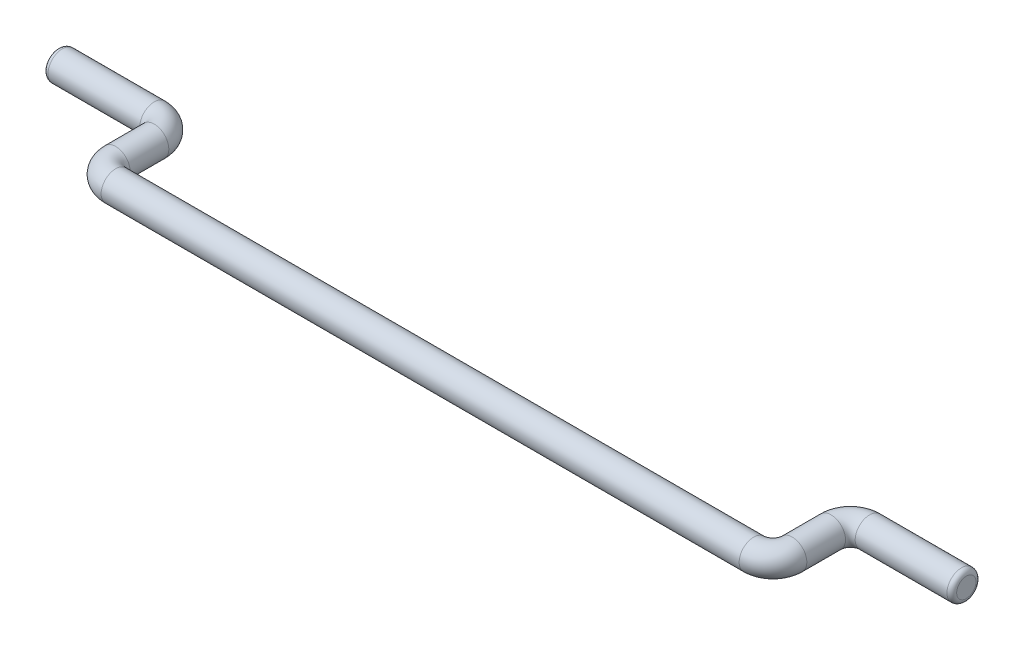
SolidWorks part; units mm, degrees
ref_plane "Front Plane" through (0, 0, 0) normal (0, 0, 1) x (1, 0, 0)
ref_plane "Top Plane" through (0, 0, 0) normal (0, 1, 0) x (1, 0, 0)
ref_plane "Right Plane" through (0, 0, 0) normal (1, 0, 0) x (0, 0, -1)
sketch "Sketch1" plane through (0, 0, 0) normal (0, 1, 0) x (1, 0, 0)
  line L0 (-6, 0) -> (-1, 0)
  line L1 (0, -1) -> (0, -3)
  line L2 (1, -4) -> (34, -4)
  line L3 (35, -3) -> (35, -1)
  line L4 (36, 0) -> (41, 0)
  arc A0 (35, -1) -> (36, 0) centre (36, -1) cw
  arc A1 (34, -4) -> (35, -3) centre (34, -3) ccw
  arc A2 (0, -3) -> (1, -4) centre (1, -3) ccw
  arc A3 (-1, 0) -> (0, -1) centre (-1, -1) cw
  point P7 (35, -2)
  point P11 (35, 0)
  point P16 (0, -4)
  point P19 (0, 0)
  dimension "D5" = 1
  dimension "D1" = 35
  dimension "D2" = 4
  dimension "D3" = 6
  dimension "D4" = 6
ref_plane "Plane1" through (-6, 0, 0) normal (1, 0, 0) x (0, 0, -1)
sketch "Sketch3" plane through (-6, 0, 0) normal (1, 0, 0) x (0, 0, -1)
  circle A0 centre (0, 0) radius 0.75
  dimension "D1" = 1.5
sweep "Sweep1" add profiles "Sketch3" path "Sketch1"
fillet "Fillet1" radius 0.25 2 edges at (41, 0, -0.75) (-6, 0, -0.75)
